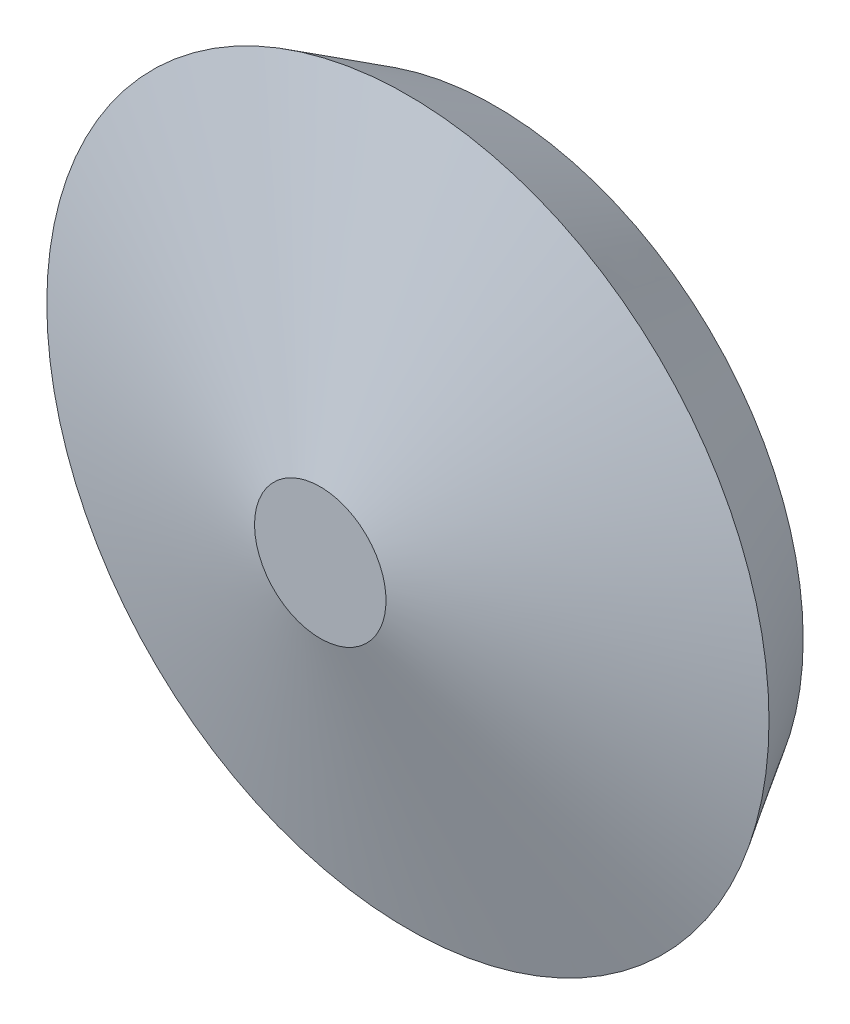
SolidWorks part; units mm, degrees
ref_plane "Front Plane" through (0, 0, 0) normal (1, 0, 0) x (0, 1, 0)
ref_plane "Top Plane" through (0, 0, 0) normal (0, 0, 1) x (0, 1, 0)
ref_plane "Right Plane" through (0, 0, 0) normal (0, 1, 0) x (-1, 0, 0)
sketch "Sketch1" plane through (0, 0, 0) normal (0, 0, 1) x (0, 1, 0)
  circle A0 centre (0, 0) radius 175.5
  dimension "D1" = 351
ref_plane "Plane1" through (0, 0, 50) normal (0, 0, 1) x (0, 1, 0)
sketch "Sketch2" plane through (0, 0, 50) normal (0, 0, 1) x (0, 1, 0)
  circle A0 centre (0, 0) radius 206
  dimension "D1" = 412
ref_plane "Plane2" through (0, 0, 100) normal (0, 0, 1) x (0, 1, 0)
sketch "Sketch3" plane through (0, 0, 100) normal (0, 0, 1) x (0, 1, 0)
  circle A0 centre (0, 0) radius 37.5
  dimension "D1" = 75
loft "Loft1" add profiles "Sketch1", "Sketch2"
sketch "Sketch4" plane through (0, 0, 50) normal (0, 0, 1) x (1, 0, 0)
  circle A1 centre (0, 0) radius 206
  circle A2 centre (0, 0) radius 206
  dimension "D1" = 0
loft "Loft4" add profiles "Sketch3", "Sketch4"
